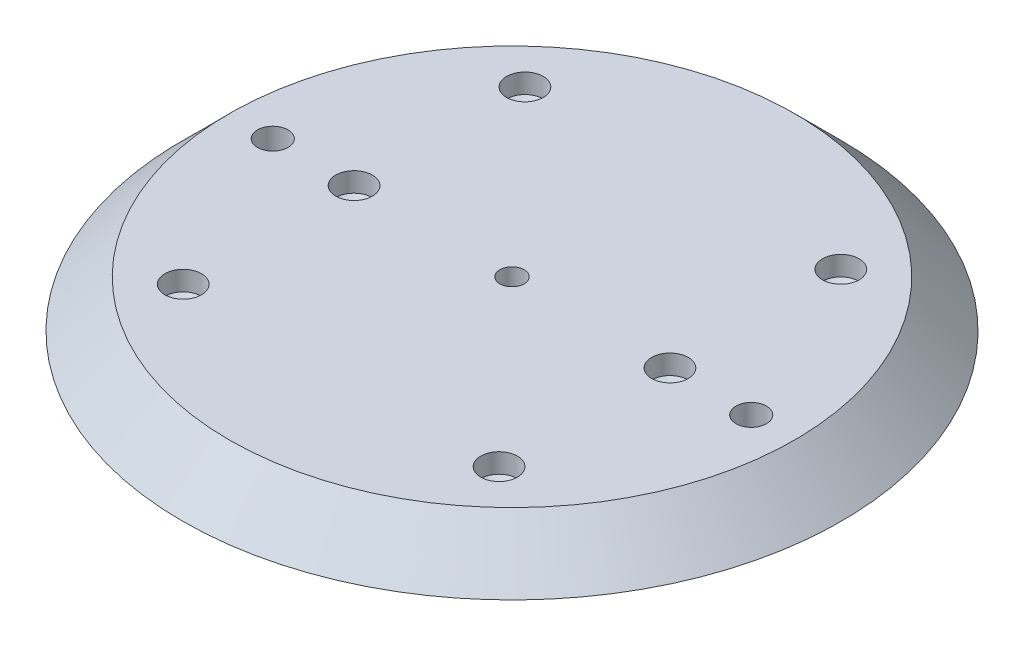
SolidWorks part; units mm, degrees
material "Malleable Cast Iron"
ref_plane "Front Plane" through (0, 0, 0) normal (0, 0, 1) x (1, 0, 0)
ref_plane "Top Plane" through (0, 0, 0) normal (0, 1, 0) x (1, 0, 0)
ref_plane "Right Plane" through (0, 0, 0) normal (1, 0, 0) x (0, 0, -1)
sketch "Sketch10" plane through (0, 0, 0) normal (0, 1, 0) x (1, 0, 0)
  line B0 (-31.369, -69.0517) -> (-31.369, 69.0517) construction
  line B1 (50.8, -69.0517) -> (50.8, 69.0517) construction
  line B2 (-50.8, -69.0517) -> (-50.8, 69.0517) construction
  line B3 (50.8, 69.0517) -> (-50.8, 69.0517) construction
  line B4 (31.369, 69.0517) -> (31.369, -69.0517) construction
  circle B5 centre (0, 0) radius 85.725
  line B6 (-31.369, 0) -> (31.369, 0) construction
  line B7 (41.0845, -69.0517) -> (41.0845, 69.0517) construction
  line B8 (31.369, 0) -> (50.8, 0) construction
  line B9 (-31.369, 0) -> (-50.8, 0) construction
  line B10 (-41.0845, 44.45) -> (41.0845, -44.45) construction
  line B11 (-41.0845, -69.0517) -> (-41.0845, 69.0517) construction
  line B12 (-41.0845, -44.45) -> (41.0845, 44.45) construction
  line B13 (-50.8, 0) -> (-85.725, 0) construction
  line B14 (50.8, 0) -> (85.725, 0) construction
  line B15 (0, -85.725) -> (0, 85.725) construction
sketch_block_instance "swivel plate-1"
sketch_block "swivel plate" parameters "D1"=171.45, "D2"=32.9884, "D3"=88.1371, "D4"=89.3617, "D5"=152.4754
sketch "Sketch1" plane through (0, 0, 0) normal (0, 1, 0) x (1, 0, 0)
  circle A0 centre (0, 0) radius 85.725 construction
  circle A1 centre (0, 0) radius 85.725
extrude "Boss-Extrude1" add sketch "Sketch1" along normal blind 12.192 draft 45
hole_wizard "3/8-16 Tapped Hole1" positions "Sketch6" profile "Sketch7" tap size "3/8-16" standard "ANSI Inch" end condition through all
sketch "Sketch6" plane through (0, 12.192, 0) normal (0, 1, 0) x (-0.9997, 0, -0.0242)
  point P13 (62.2117, 1.5089)
  point P15 (-62.2117, -1.5089)
sketch "Sketch7" plane through (-62.23, 12.192, 0) normal (1, 0, 0) x (0, 0, 1)
  line L0 (0, 0) -> (0, 12.192)
  line L1 (0, 12.192) -> (3.9687, 12.192)
  line L2 (3.9687, 12.192) -> (3.9687, 0)
  line L5 (3.9687, 0) -> (0, 0)
  line L11 (0, -6.35) -> (0, 107.95) construction
  dimension "Thru Tap Drill Dia." = 7.9375
  dimension "Thru Tap Drill Depth" = 12.192
cosmetic thread "Hole Thread1"
cosmetic thread "Hole Thread2"
hole_wizard "1/4 (0.25) Press Dowel Hole1" positions "Sketch8" profile "Sketch9" hole size "1/4" standard "ANSI Inch" end condition through all
sketch "Sketch8" plane through (-177.9915, 12.192, 193.466) normal (0, 1, 0) x (-0.9096, 0, -0.4155)
  point P2 (-81.5106, -249.9322)
sketch "Sketch9" plane through (0, 12.192, 0) normal (1, 0, 0) x (0, 0, 1)
  line L0 (0, 0) -> (0, 12.192)
  line L1 (0, 12.192) -> (3.175, 12.192)
  line L2 (3.175, 12.192) -> (3.175, 0)
  line L3 (3.175, 0) -> (0, 0)
  line L4 (0, -6.35) -> (0, 107.95) construction
  dimension "Thru Hole Dia." = 6.35
  dimension "Thru Hole Depth" = 12.192
hole_wizard "3/8 (0.375) Diameter Hole1" positions "Sketch12" profile "Sketch11" hole size "3/8" standard "ANSI Inch"
sketch "Sketch12" plane through (0, 12.192, 0) normal (0, 1, 0) x (1, 0, 0)
  point P4 (-41.0845, 44.45)
  point P6 (-41.0845, 0)
  point P8 (-41.0845, -44.45)
  point P10 (41.0845, -44.45)
  point P12 (41.0845, 0)
  point P14 (41.0845, 44.45)
sketch "Sketch11" plane through (-41.0845, 12.192, -44.45) normal (1, 0, 0) x (0, 0, 1)
  line L0 (0, 0) -> (0, 7.9416)
  line L1 (0, 7.9416) -> (4.7625, 5.08)
  line L2 (4.7625, 5.08) -> (4.7625, 0)
  line L5 (4.7625, 0) -> (0, 0)
  line L10 (0, 7.9416) -> (-4.7625, 5.08) construction
  line L11 (0, -6.35) -> (0, 107.95) construction
  dimension "Hole Dia." = 9.525
  dimension "Hole Depth" = 5.08
  dimension "Drill Angle" = 118
equation "\"delta-z\" = 1.5"
equation "\"total-height\" = 3.28"
equation "\"mid-height\" = 1.5"
equation "\"jaw-width\" = 4"
equation "\"jaw-height\" = \"total-height\" - \"mid-height\""
equation "\"max-tube-diam\" = 3.5"
equation "\"v-block-notch-height\" = 1.5"
equation "\"v-block-notch-angle\" = 120"
equation "\"jaw-travel\" = 4.45"
equation "\"rib-top-width\" = 0.5"
equation "\"rib-side-width\" = 0.5"
equation "\"quarter-twenty-close-clearance\" = .257"
equation "\"box-way-width\" = 1.5"
equation "\"box-way-depth\" = 1.5"
equation "\"screw-OD\" = .625"
equation "\"screw-reduced-diam\" = .47"
equation "\"pressure-plate-OD\" = 6.75"
equation "\"swivel-cleat-thick\" = .5"
equation "\"swivel-gap\" = .02"
equation "\"D1@Boss-Extrude1\"=\"swivel-cleat-thick\" - \"swivel-gap\""
equation "\"D1@swivel plate\"=\"pressure-plate-OD\""
equation "\"D2@swivel plate\"=\"jaw-width\""
equation "\"D3@swivel plate\"=2.47"
